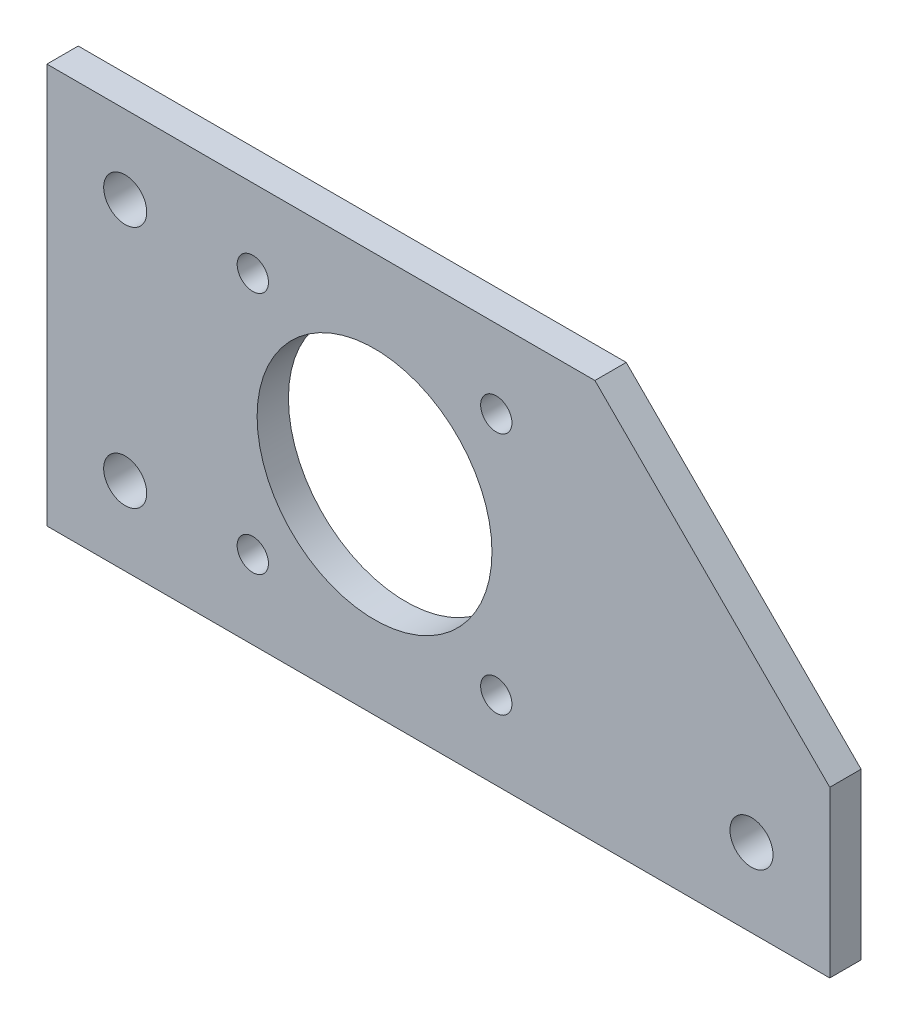
SolidWorks part; units mm, degrees
ref_plane "Front" through (0, 0, 0) normal (0, 0, 1) x (1, 0, 0)
ref_plane "Top" through (0, 0, 0) normal (0, 1, 0) x (1, 0, 0)
ref_plane "Right" through (0, 0, 0) normal (1, 0, 0) x (0, 0, -1)
sketch "Sketch1" plane through (0, 0, 0) normal (0, 0, 1) x (1, 0, 0)
  line L0 (-31.5, 0) -> (0, 0) construction
  line L1 (-31.5, 21.15) -> (31.5, 21.15) construction
  line L2 (-31.5, 21.15) -> (-31.5, -21.15)
  line L3 (-31.5, -21.15) -> (31.5, -21.15) construction
  line L4 (31.5, 21.15) -> (31.5, -21.15)
  line L5 (0, 0) -> (31.5, 0) construction
  line L6 (-31.5, 21.15) -> (-31.5, 25.55)
  line L7 (-31.5, 25.55) -> (31.5, 25.55)
  line L8 (31.5, 25.55) -> (31.5, 21.15)
  line L9 (-31.5, -21.15) -> (-31.5, -25.55)
  line L10 (-31.5, -25.55) -> (31.5, -25.55)
  line L11 (31.5, -25.55) -> (31.5, -21.15)
  dimension "D1" = 42.3
  dimension "D2" = 63
  dimension "D3" = 4.4
extrude "Boss-Extrude1" add sketch "Sketch1" along normal blind 4
sketch "Sketch2" plane through (0, 0, 4) normal (0, 0, 1) x (1, 0, 0)
  line L0 (-5.2, 15.55) -> (25.9, 15.55) construction
  line L1 (25.9, 15.55) -> (25.9, -15.55) construction
  line L2 (-5.2, -15.55) -> (25.9, -15.55) construction
  line L3 (25.9, 15.55) -> (25.9, 25.55) construction
  line L4 (31.5, 25.55) -> (-31.5, 25.55) construction
  line L5 (25.9, 15.55) -> (31.5, 15.55) construction
  line L6 (31.5, -25.55) -> (31.5, 25.55) construction
  line L7 (25.9, -15.55) -> (25.9, -25.55) construction
  line L8 (-31.5, -25.55) -> (31.5, -25.55) construction
  line L9 (-21.5, 15.55) -> (-21.5, -15.55) construction
  line L10 (-21.5, 15.55) -> (-31.5, 15.55) construction
  line L11 (-31.5, 25.55) -> (-31.5, -25.55) construction
  line L12 (-21.5, -15.55) -> (-31.5, -15.55) construction
  line L13 (-21.5, 15.55) -> (-21.5, 25.55) construction
  line L14 (10.35, 15.55) -> (10.35, 0) construction
  line L15 (10.35, 0) -> (25.9, 0) construction
  circle A0 centre (-5.2, 15.55) radius 2
  circle A1 centre (25.9, 15.55) radius 2
  circle A2 centre (25.9, -15.55) radius 2
  circle A3 centre (-5.2, -15.55) radius 2
  circle A4 centre (-21.5, 15.55) radius 2.75
  circle A5 centre (-21.5, -15.55) radius 2.75
  circle A6 centre (10.35, 0) radius 15
  dimension "D2" = 4
  dimension "D3" = 5.5
  dimension "D5" = 30
  dimension "D1" = 31.1
  dimension "D4" = 10
  dimension "D6" = 5.6
extrude "Cut-Extrude1" cut sketch "Sketch2" against normal up to next
sketch "Sketch4" plane through (31.5, 0, 0) normal (1, 0, 0) x (0, 0, -1)
  line L0 (-4, -25.55) -> (-4, 25.55) construction
  line L1 (-4, -25.55) -> (0, -25.55) construction
  line L2 (0, -25.55) -> (0, 25.55) construction
  line L3 (-4, 25.55) -> (0, 25.55) construction
  line L4 (-4, -25.55) -> (-4, 25.55)
  line L5 (-4, -25.55) -> (0, -25.55)
  line L6 (0, -25.55) -> (0, 25.55)
  line L7 (-4, 25.55) -> (0, 25.55)
extrude "Boss-Extrude2" add sketch "Sketch4" along normal blind 37
sketch "Sketch5" plane through (0, 0, 4) normal (0, 0, 1) x (1, 0, 0)
  line L0 (58.5, -15.55) -> (58.5, -25.55) construction
  line L1 (-31.5, -25.55) -> (68.5, -25.55) construction
  line L2 (58.5, -15.55) -> (68.5, -15.55) construction
  line L4 (68.5, 25.55) -> (68.5, -25.55) construction
  line L5 (-31.5, -15.55) -> (-21.5, -15.55) construction
  line L6 (-31.5, 25.55) -> (-31.5, -25.55) construction
  circle A0 centre (58.5, -15.55) radius 2.75
  circle A1 centre (-21.5, -15.55) radius 2.75 construction
extrude "Cut-Extrude2" cut sketch "Sketch5" against normal up to next
chamfer "Chamfer2" distance 30 angle 45 1 edges at (68.5, 25.55, 2)
